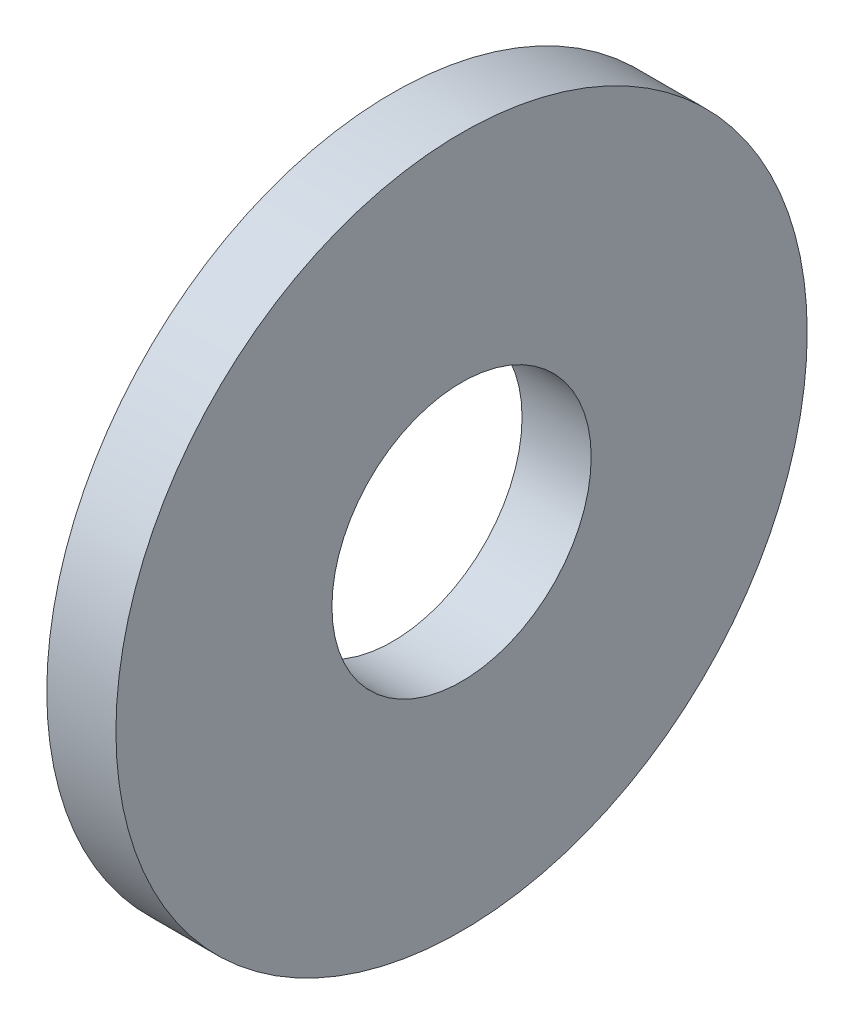
SolidWorks part; units mm, degrees
ref_plane "Front Plane" through (0, 0, 0) normal (0, 0, 1) x (1, 0, 0)
ref_plane "Top Plane" through (0, 0, 0) normal (0, 1, 0) x (1, 0, 0)
ref_plane "Right Plane" through (0, 0, 0) normal (1, 0, 0) x (0, 0, -1)
sketch "Sketch1" plane through (0, 0, 0) normal (1, 0, 0) x (0, 0, -1)
  circle A0 centre (0, 0) radius 4.7625
  circle A1 centre (0, 0) radius 12.7
  dimension "D1" = 9.525
  dimension "D2" = 25.4
extrude "Boss-Extrude1" add sketch "Sketch1" along normal blind 2.54
